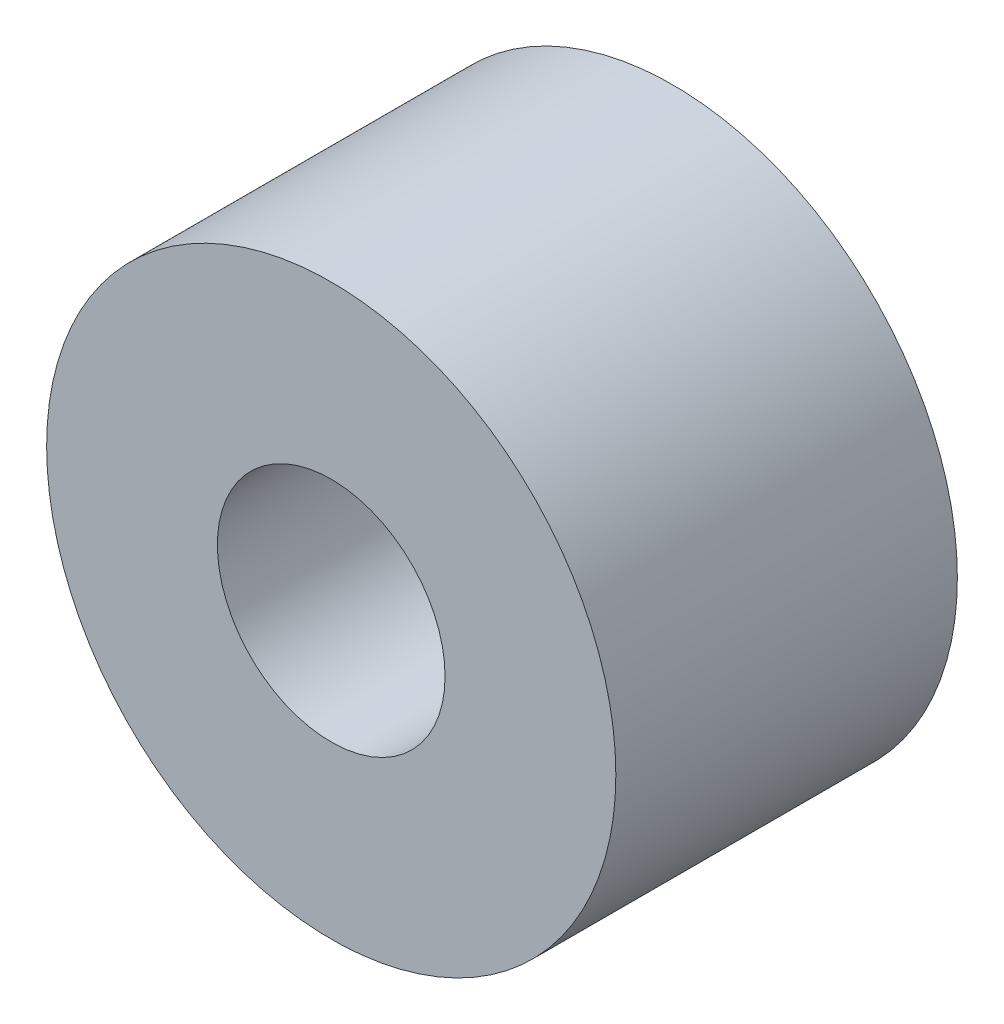
SolidWorks part; units mm, degrees
ref_plane "Front Plane" through (0, 0, 0) normal (0, 0, 1) x (1, 0, 0)
ref_plane "Top Plane" through (0, 0, 0) normal (0, 1, 0) x (1, 0, 0)
ref_plane "Right Plane" through (0, 0, 0) normal (1, 0, 0) x (0, 0, -1)
sketch "Sketch1" plane through (0, 0, 0) normal (0, 0, 1) x (1, 0, 0)
  circle A0 centre (0, 0) radius 2.5
  circle A1 centre (0, 0) radius 1
  dimension "D1" = 2
  dimension "D2" = 5
extrude "Boss-Extrude1" add sketch "Sketch1" along normal blind 3
